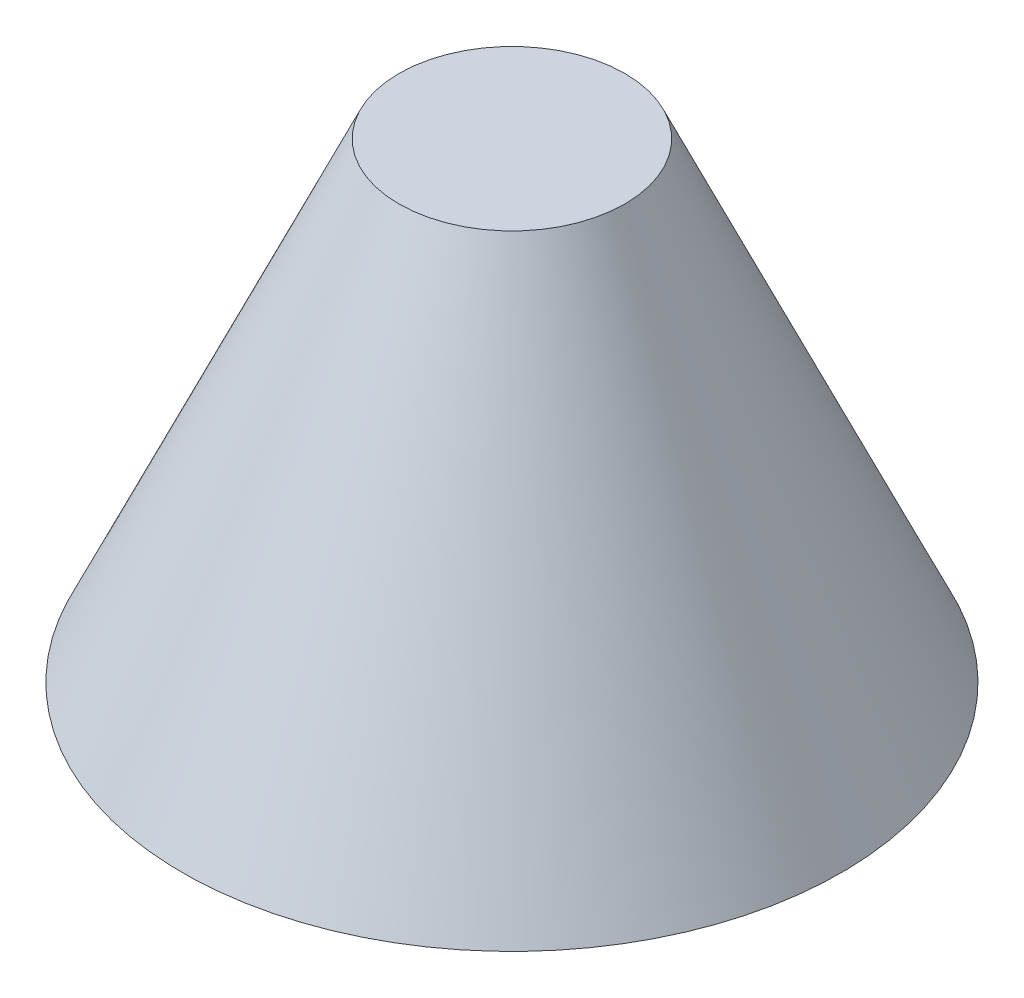
SolidWorks part; units mm, degrees
ref_plane "Front Plane" through (0, 0, 0) normal (0, 0, 1) x (1, 0, 0)
ref_plane "Top Plane" through (0, 0, 0) normal (0, 1, 0) x (1, 0, 0)
ref_plane "Right Plane" through (0, 0, 0) normal (1, 0, 0) x (0, 0, -1)
sketch "草图3" plane through (0, 0, 0) normal (0, 0, 1) x (1, 0, 0)
  line L0 (0, 0) -> (35, 0)
  line L1 (35, 0) -> (12, 50)
  line L2 (12, 50) -> (0, 50)
  line L3 (0, 50) -> (0, 0)
  line L4 (0, 0) -> (0, 50) construction
  dimension "bottom_radius" = 35
  dimension "top_radius" = 12
  dimension "height" = 50
revolve "Shade" add sketch "草图3" angle 360 about L4
